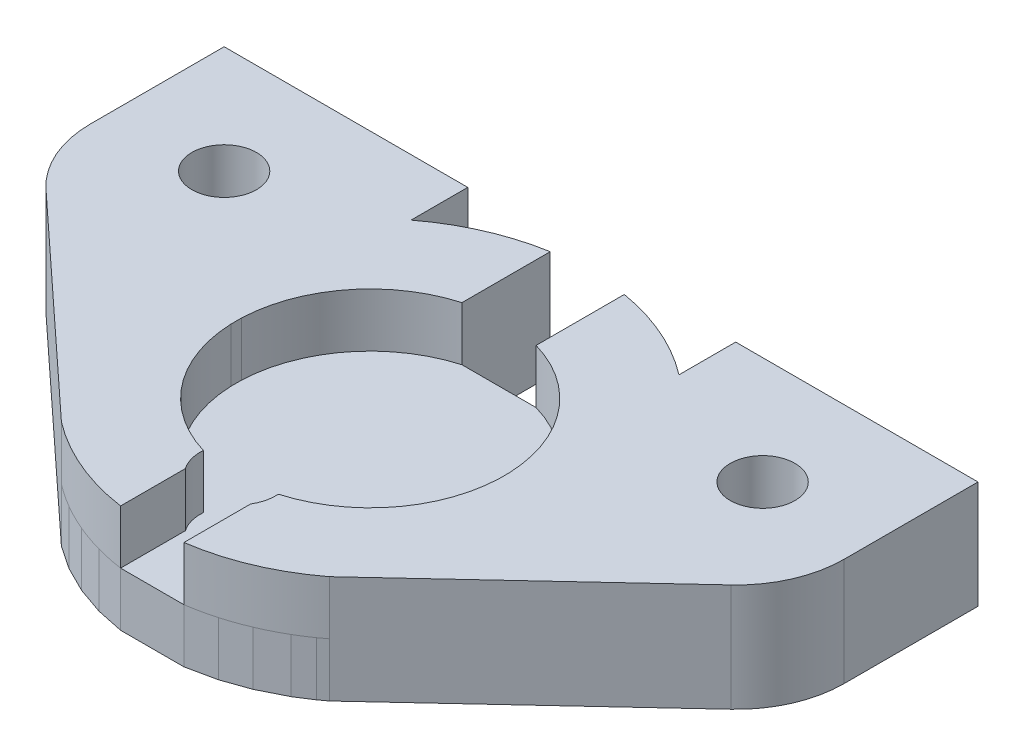
SolidWorks part; units mm, degrees
ref_plane "前基準面" through (0, 0, 0) normal (0, 0, 1) x (1, 0, 0)
ref_plane "上基準面" through (0, 0, 0) normal (0, 1, 0) x (1, 0, 0)
ref_plane "右基準面" through (0, 0, 0) normal (1, 0, 0) x (0, 0, -1)
sketch "草圖1" plane through (0, 0, 0) normal (0, 1, 0) x (1, 0, 0)
  line L1 (-35, 21.5) -> (35, 21.5)
  line L2 (-35, 21.5) -> (-35, -21.5)
  line L3 (-35, -21.5) -> (35, -21.5)
  line L4 (35, 21.5) -> (35, -21.5)
  line L5 (-35, 21.5) -> (35, -21.5) construction
  line L6 (-35, -21.5) -> (35, 21.5) construction
  point P0 (0, 0)
  dimension "D1" = 70
  dimension "D2" = 43
extrude "填料-伸長1" add sketch "草圖1" along normal blind 10
sketch "草圖8" plane through (0, 0, 21.5) normal (0, 0, 1) x (1, 0, 0)
  line L0 (-1035, 5) -> (48965, 5) construction
  line L1 (-35, 10) -> (-35, 0) construction
  line L2 (0, -990) -> (0, 49010) construction
  line L3 (-35, 10) -> (35, 10) construction
  line L4 (35, 10) -> (35, 0) construction
  line L5 (-12.38, 10) -> (12.5, 10)
  line L6 (-12.38, 10) -> (-12.38, 5)
  line L7 (-12.38, 5) -> (12.5, 5)
  line L8 (12.5, 10) -> (12.5, 5)
  point P5 (-35, 5)
  point P10 (0, 10)
  dimension "D1" = 24.88
  dimension "D2" = 22.5
extrude "除料-伸長4" cut sketch "草圖8" against normal through all
sketch "草圖11" plane through (0, 5, 0) normal (0, 1, 0) x (1, 0, 0)
  line L0 (0.06, -978.5) -> (0.06, 49021.5) construction
  line L1 (-12.38, 21.5) -> (12.5, 21.5) construction
  line L2 (-1012.38, 0) -> (48987.62, 0) construction
  line L3 (-12.38, 21.5) -> (-12.38, -21.5) construction
  circle A0 centre (0.06, 0) radius 12.45
  point P5 (0.06, 21.5)
  point P10 (-12.38, 0)
  dimension "D1" = 24.9
extrude "伸長-薄件1" add sketch "草圖11" along normal blind 5 and the other way blind 2 thin
sketch "草圖14" plane through (0, 5, 0) normal (0, 1, 0) x (1, 0, 0)
  line L0 (0.06, -20.45) -> (12.5, -20.45)
  line L1 (12.5, -16.2311) -> (12.5, -21.5) construction
  line L2 (12.5, -20.45) -> (12.5, -21.5)
  line L3 (12.5, -21.5) -> (-12.38, -21.5)
  line L4 (-12.38, -21.5) -> (-12.38, -20.45)
  line L5 (-12.38, -16.2311) -> (-12.38, -21.5) construction
  line L6 (-12.38, -20.45) -> (0.06, -20.45)
  arc A0 (-12.38, -16.2311) -> (12.5, -16.2311) centre (0.06, 0) ccw construction
extrude "除料-伸長6" cut sketch "草圖14" against normal blind 5
sketch "草圖15" plane through (0, 5, 0) normal (0, 1, 0) x (1, 0, 0)
  line L0 (0.06, 20.45) -> (12.5, 20.45)
  line L1 (12.5, 21.5) -> (12.5, 16.2311) construction
  line L2 (12.5, 20.45) -> (12.5, 21.5)
  line L3 (12.5, 21.5) -> (-12.38, 21.5)
  line L4 (-12.38, 21.5) -> (-12.38, 20.45)
  line L5 (-12.38, 21.5) -> (-12.38, 16.2311) construction
  line L6 (-12.38, 20.45) -> (0.06, 20.45)
  arc A0 (12.5, 16.2311) -> (-12.38, 16.2311) centre (0.06, 0) ccw construction
extrude "除料-伸長7" cut sketch "草圖15" against normal blind 5
sketch "草圖16" plane through (0, 10, 0) normal (0, 1, 0) x (1, 0, 0)
  line L0 (0.06, -987.55) -> (0.06, 49012.45) construction
  line L2 (-2.88, 23.0979) -> (3, 23.0979)
  line L3 (-2.88, 23.0979) -> (-2.88, 12.0979)
  line L4 (-2.88, 12.0979) -> (3, 12.0979)
  line L5 (3, 23.0979) -> (3, 12.0979)
  line L6 (-2.88, 23.0979) -> (3, 12.0979) construction
  line L7 (-2.88, 12.0979) -> (3, 23.0979) construction
  arc A0 (12.5, 0.4989) -> (-12.38, 0.4989) centre (0.06, 0) ccw construction
  point P1 (0.06, 17.5979)
  point P6 (0.06, 12.45)
  dimension "D1" = 5.88
  dimension "D2" = 11
extrude "除料-伸長8" cut sketch "草圖16" against normal blind 5
sketch "草圖17" plane through (0, 10, 0) normal (0, 1, 0) x (1, 0, 0)
  line L0 (-2.88, -987.9021) -> (-2.88, 49012.0979) construction
  line L1 (3, -987.9021) -> (3, 49012.0979) construction
  line L2 (12.5, -20.45) -> (0.06, -20.45) construction
  line L3 (-2.88, -12.0979) -> (3, -12.0979)
  line L4 (-2.88, -12.0979) -> (-2.88, -20.45)
  line L5 (-2.88, -20.45) -> (3, -20.45)
  line L6 (3, -12.0979) -> (3, -20.45)
  arc A0 (-12.38, -0.4989) -> (12.5, -0.4989) centre (0.06, 0) ccw construction
extrude "除料-伸長9" cut sketch "草圖17" against normal blind 5
sketch "草圖19" plane through (0, 5, 0) normal (0, 1, 0) x (1, 0, 0)
  line L0 (-2.88, 20.2376) -> (-2.88, 20.45)
  line L1 (-12.38, 20.45) -> (12.5, 20.45) construction
  line L2 (-2.88, 20.45) -> (2.9876, 20.45)
  line L3 (2.9876, 20.45) -> (3, 20.2376)
  line L4 (3, 12.0979) -> (3, 20.2376) construction
  line L5 (3, 20.2376) -> (-2.88, 20.2376)
  arc A0 (12.5, 16.2311) -> (3, 20.2376) centre (0.06, 0) ccw construction
extrude "除料-伸長10" cut sketch "草圖19" against normal blind 5
sketch "草圖20" plane through (0, 5, 0) normal (0, 1, 0) x (1, 0, 0)
  line L0 (3, -20.2376) -> (3, -20.45)
  line L1 (12.5, -20.45) -> (-12.38, -20.45) construction
  line L2 (3, -20.45) -> (-2.8878, -20.45)
  line L3 (-2.8878, -20.45) -> (-2.88, -20.2376)
  line L4 (-2.88, -20.2376) -> (3, -20.2376)
extrude "除料-伸長11" cut sketch "草圖20" against normal blind 5
sketch "草圖21" plane through (0, 10, 0) normal (0, 1, 0) x (1, 0, 0)
  line L0 (-12.38, 21.5) -> (-35, 21.5) construction
  line L1 (-35, 21.5) -> (-35, -21.5) construction
  circle A0 centre (-25, 11.5) radius 3
  dimension "D1" = 10
  dimension "D2" = 10
  dimension "D3" = 6
extrude "除料-伸長12" cut sketch "草圖21" against normal through all
sketch "草圖22" plane through (0, 10, 0) normal (0, 1, 0) x (1, 0, 0)
  line L0 (35, 21.5) -> (12.5, 21.5) construction
  line L1 (35, -21.5) -> (35, 21.5) construction
  circle A0 centre (25, 11.5) radius 3
  dimension "D1" = 10
  dimension "D2" = 10
  dimension "D3" = 6
extrude "除料-伸長13" cut sketch "草圖22" against normal through all
sketch "草圖24" plane through (0, 5, 0) normal (0, 1, 0) x (1, 0, 0)
  circle A0 centre (0, -12.2162) radius 3.51
  dimension "D1" = 7.02
extrude "除料-伸長15" cut sketch "草圖24" along normal blind 7
sketch "草圖27" plane through (0, 5, 0) normal (0, 1, 0) x (1, 0, 0)
  line L1 (-2.88, 20.2376) -> (3, 20.2376)
  line L2 (-2.88, 20.2376) -> (-2.88, 12.0979)
  line L3 (-2.88, 12.0979) -> (3, 12.0979)
  line L4 (3, 20.2376) -> (3, 12.0979)
extrude "除料-伸長16" cut sketch "草圖27" against normal blind 7
sketch "草圖31" plane through (0, 10, 0) normal (0, 1, 0) x (1, 0, 0)
  line L0 (-2.88, 16.8435) -> (-3.38, 16.8435) construction
  line L1 (-2.88, 20.2376) -> (-2.88, 12.0979) construction
  line L2 (3, 16.1677) -> (3.5, 16.1677) construction
  line L3 (3, 12.0979) -> (3, 20.2376) construction
  line L4 (-12.38, 20.45) -> (-2.88, 20.45) construction
  line L5 (3.5, 11.9653) -> (-3.38, 11.9653)
  line L6 (3.5, 11.9653) -> (3.5, 20.45)
  line L7 (3.5, 20.45) -> (-3.38, 20.45)
  line L8 (-3.38, 11.9653) -> (-3.38, 20.45)
  arc A0 (12.5, 0.4989) -> (3, 12.0979) centre (0.06, 0) ccw construction
  dimension "D1" = 0.5
  dimension "D2" = 0.5
extrude "除料-伸長21" cut sketch "草圖31" against normal blind 14.5
sketch "草圖32" plane through (0, 5, 0) normal (0, 1, 0) x (1, 0, 0)
  line L0 (12.5, 20.45) -> (12.5, 16.2311)
  line L1 (12.5, 16.2311) -> (10.4227, 17.63)
  line L2 (10.4227, 17.63) -> (8.2392, 18.7431)
  line L3 (8.2392, 18.7431) -> (5.9577, 19.5811)
  line L4 (5.9577, 19.5811) -> (3.5, 20.1586)
  line L5 (3.5, 20.1586) -> (3.5, 20.45)
  line L6 (3.5, 20.45) -> (12.5, 20.45)
  arc A0 (12.5, 16.2311) -> (3.5, 20.1586) centre (0.06, 0) ccw construction
  arc A1 (12.5, 16.2311) -> (3.5, 20.1586) centre (0.06, 0) ccw construction
extrude "除料-伸長22" cut sketch "草圖32" against normal through all
sketch "草圖33" plane through (0, 5, 0) normal (0, 1, 0) x (1, 0, 0)
  line L0 (-12.38, 16.2311) -> (-12.38, 20.45)
  line L1 (-12.38, 20.45) -> (-3.38, 20.45)
  line L2 (-3.38, 20.45) -> (-3.38, 20.1586)
  line L3 (-3.38, 20.1586) -> (-5.7873, 19.5962)
  line L4 (-5.7873, 19.5962) -> (-8.1192, 18.7431)
  line L5 (-8.1192, 18.7431) -> (-10.3382, 17.6091)
  line L6 (-10.3382, 17.6091) -> (-12.38, 16.2311)
  arc A0 (-3.38, 20.1586) -> (-12.38, 16.2311) centre (0.06, 0) ccw construction
  arc A1 (-3.38, 20.1586) -> (-12.38, 16.2311) centre (0.06, 0) ccw construction
extrude "除料-伸長23" cut sketch "草圖33" against normal through all
sketch "草圖34" plane through (0, 5, 0) normal (0, 1, 0) x (1, 0, 0)
  line L0 (-12.38, -20.45) -> (-12.38, -16.2311)
  line L1 (-12.38, -16.2311) -> (-10.2151, -17.6812)
  line L2 (-10.2151, -17.6812) -> (-7.8866, -18.8429)
  line L3 (-7.8866, -18.8429) -> (-5.4206, -19.7019)
  line L4 (-5.4206, -19.7019) -> (-2.88, -20.2376)
  line L5 (-2.88, -20.2376) -> (-2.8878, -20.45)
  line L6 (-2.88, -20.2376) -> (-2.8878, -20.45) construction
  line L7 (-2.8878, -20.45) -> (-12.38, -20.45) construction
  line L8 (-2.8878, -20.45) -> (-12.38, -20.45)
  arc A0 (-12.38, -16.2311) -> (-2.88, -20.2376) centre (0.06, 0) ccw construction
extrude "除料-伸長24" cut sketch "草圖34" against normal through all
sketch "草圖35" plane through (0, 5, 0) normal (0, 1, 0) x (1, 0, 0)
  line L0 (3, -20.2376) -> (3, -20.45)
  line L1 (3, -20.45) -> (3, -20.2376) construction
  line L2 (12.5, -20.45) -> (3, -20.45) construction
  line L3 (3, -20.45) -> (12.5, -20.45)
  line L4 (12.5, -20.45) -> (12.5, -16.2311)
  line L5 (12.5, -16.2311) -> (11.8026, -16.7426)
  line L6 (11.8026, -16.7426) -> (10.3761, -17.6573)
  line L7 (10.3761, -17.6573) -> (8.0066, -18.8429)
  line L8 (8.0066, -18.8429) -> (5.6507, -19.671)
  line L9 (5.6507, -19.671) -> (3, -20.2376)
  arc A0 (3, -20.2376) -> (12.5, -16.2311) centre (0.06, 0) ccw construction
  arc A1 (3, -20.2376) -> (12.5, -16.2311) centre (0.06, 0) ccw construction
extrude "除料-伸長25" cut sketch "草圖35" against normal blind 14.5
sketch "草圖37" plane through (0, 10, 0) normal (0, 1, 0) x (1, 0, 0)
  line L0 (-35, -21.5) -> (-12.38, -21.5)
  line L1 (-12.38, -21.5) -> (-12.38, -16.2311)
  line L2 (-12.38, -16.2311) -> (-35, 4.7207)
  line L3 (-35, 21.5) -> (-35, -21.5) construction
  line L4 (-35, 4.7207) -> (-35, -21.5)
extrude "除料-伸長26" cut sketch "草圖37" against normal blind 14.5
sketch "草圖38" plane through (0, 10, 0) normal (0, 1, 0) x (1, 0, 0)
  line L0 (-1035, 4.7207) -> (48965, 4.7207) construction
  line L1 (35, 4.7207) -> (35, -21.5)
  line L2 (35, -21.5) -> (35, 21.5) construction
  line L3 (35, -21.5) -> (12.5, -21.5)
  line L4 (12.5, -21.5) -> (12.5, -16.2311)
  line L5 (12.5, -16.2311) -> (35, 4.7207)
extrude "除料-伸長27" cut sketch "草圖38" against normal blind 14.5
fillet "圓角1" radius 10 2 edges at (35, 5, -4.7207) (-35, 5, -4.7207)
